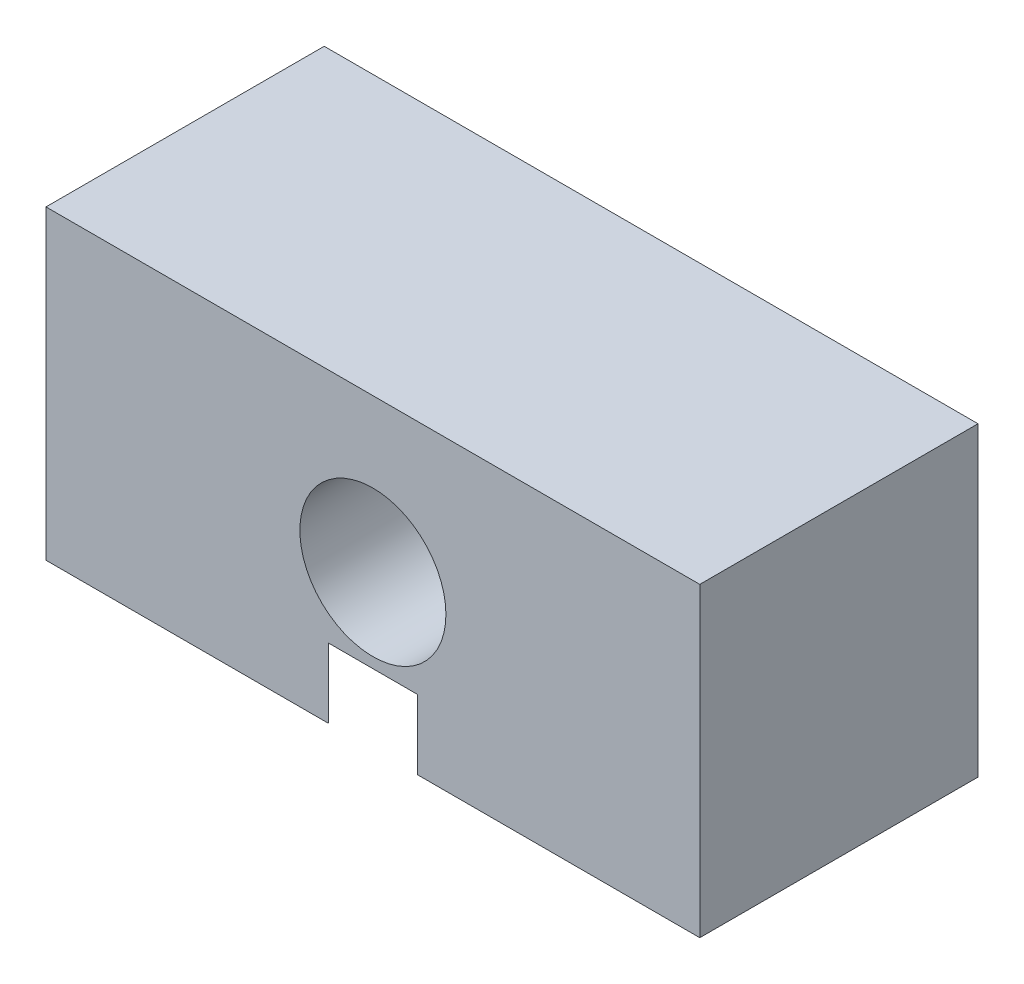
SolidWorks part; units mm, degrees
ref_plane "Front Plane" through (0, 0, 0) normal (0, 0, 1) x (1, 0, 0)
ref_plane "Top Plane" through (0, 0, 0) normal (0, 1, 0) x (1, 0, 0)
ref_plane "Right Plane" through (0, 0, 0) normal (1, 0, 0) x (0, 0, -1)
sketch "Sketch1" plane through (0, 0, 0) normal (0, 0, 1) x (1, 0, 0)
  line L1 (-23.5, -11) -> (23.5, -11)
  line L2 (-23.5, -11) -> (-23.5, 11)
  line L3 (-23.5, 11) -> (23.5, 11)
  line L4 (23.5, -11) -> (23.5, 11)
  line L5 (-23.5, -11) -> (23.5, 11) construction
  line L6 (-23.5, 11) -> (23.5, -11) construction
  circle A0 centre (0, 0) radius 5.25
  point P0 (0, 0)
  dimension "D3" = 10.5
  dimension "D1" = 47
  dimension "D2" = 22
extrude "Boss-Extrude1" add sketch "Sketch1" along normal blind 20
sketch "Sketch2" plane through (0, -11, 0) normal (0, -1, 0) x (1, 0, 0)
  line L1 (10.0049, 6.8138) -> (15.5669, 6.8138)
  line L2 (10.0049, 6.8138) -> (10.0049, 13.5375)
  line L3 (10.0049, 13.5375) -> (15.5669, 13.5375)
  line L4 (15.5669, 6.8138) -> (15.5669, 13.5375)
  circle A0 centre (0, 10) radius 10.5
  line M2 (-23.5, 0) -> (23.5, 0)
  line M4 (23.5, 20) -> (-23.5, 20)
  dimension "D1" = 21
extrude "Cut-Extrude1" cut sketch "Sketch2" against normal blind 5 contours A0 L2 M2 M4 | A0 L1 L4 L3 L2 | L2 A0
